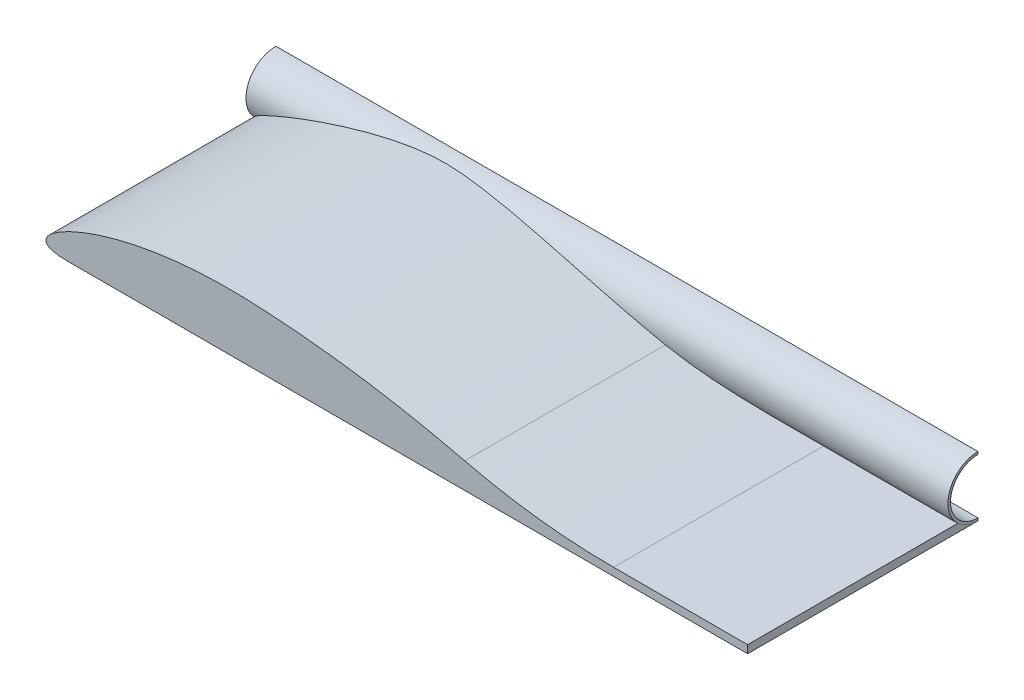
SolidWorks part; units mm, degrees
ref_plane "Front Plane" through (0, 0, 0) normal (0, 0, 1) x (1, 0, 0)
ref_plane "Top Plane" through (0, 0, 0) normal (0, 1, 0) x (1, 0, 0)
ref_plane "Right Plane" through (0, 0, 0) normal (1, 0, 0) x (0, 0, -1)
curve "Curve1"
  spline degree 3 poles (302.9843, 0.2066, 0) (305.2463, -0.0888, 0) (303.0423, 0.5058, 0) (301.2607, 1.1313, 0) (296.8595, 2.4314, 0) (291.4283, 4.0595, 0) (284.2715, 6.1062, 0) (275.7591, 8.441, 0) (265.8676, 11.0139, 0) (254.7283, 13.724, 0) (242.4522, 16.5013, 0) (229.1619, 19.2495, 0) (215.0022, 21.8919, 0) (200.1221, 24.3477, 0) (184.6818, 26.5449, 0) (168.8517, 28.4234, 0) (152.8082, 29.9307, 0) (136.7266, 31.0049, 0) (120.7051, 31.6889, 0) (104.9137, 31.6962, 0) (89.5649, 30.8862, 0) (74.9378, 29.3709, 0) (61.2207, 27.2233, 0) (48.5868, 24.554, 0) (37.1861, 21.5011, 0) (27.1553, 18.1971, 0) (18.5969, 14.8045, 0) (11.6064, 11.436, 0) (6.2054, 8.2632, 0) (2.4621, 5.3102, 0) (0.1728, 2.7181, 0) (-0.3667, -0.1067, 0) (1.6185, -2.1752, 0) (4.9031, -3.1118, 0) (9.5405, -3.659, 0) (15.6223, -3.6847, 0) (23.0877, -3.3095, 0) (31.8617, -2.5607, 0) (41.8437, -1.5362, 0) (52.932, -0.3245, 0) (65.0085, 0.9827, 0) (77.9641, 2.2775, 0) (91.674, 3.4466, 0) (106.0204, 4.4121, 0) (120.9553, 5.0518, 0) (136.3391, 5.4103, 0) (152.0077, 5.7293, 0) (167.7158, 5.8914, 0) (183.2867, 5.9078, 0) (198.553, 5.7595, 0) (213.3478, 5.4574, 0) (227.5084, 5.0134, 0) (240.8771, 4.4585, 0) (253.3023, 3.8196, 0) (264.6365, 3.1406, 0) (274.7593, 2.4517, 0) (283.5118, 1.8033, 0) (290.9024, 1.2074, 0) (296.5367, 0.7424, 0) (301.0977, 0.3102, 0) (302.9843, 0.2066, 0) (305.2463, -0.0888, 0) (303.0423, 0.5058, 0) knots -0.012269 -0.005489 -0.001366 0 0.001375 0.005484 0.012273 0.021682 0.033581 0.047831 0.064306 0.082777 0.103064 0.124929 0.148149 0.172445 0.197572 0.223269 0.249228 0.275186 0.300901 0.326463 0.351222 0.374906 0.39727 0.418072 0.43708 0.454093 0.46892 0.481392 0.491447 0.499024 0.504294 0.507922 0.51154 0.516781 0.524216 0.533992 0.546034 0.56022 0.576403 0.594371 0.613951 0.634917 0.657089 0.68023 0.704175 0.72909 0.754354 0.779668 0.80476 0.829359 0.853209 0.876041 0.897604 0.917662 0.93597 0.95231 0.966503 0.97835 0.987731 0.994511 0.998634 1 1.001375 1.005484 1.012273 periodic
sketch "Sketch1" plane through (0, 0, 0) normal (0, 0, 1) x (1, 0, 0)
  line L0 (397.4027, 0) -> (397.4027, -11.2558) construction
  line L1 (397.4027, -11.2558) -> (0, -11.2558) construction
  line L2 (0, -11.2558) -> (0, 0) construction
  line L3 (397.4027, 0) -> (397.4027, 42.136) construction
  line L4 (397.4027, 42.136) -> (0, 42.136) construction
  line L5 (0, 42.136) -> (0, 0) construction
  line L6 (16.8245, -3.584) -> (563.88, -3.584)
  line L7 (563.88, -3.584) -> (563.88, 2.766)
  line L8 (563.88, 2.766) -> (388.5279, 2.766)
  line L9 (397.4027, 0) -> (0, 0) construction
  spline S1 degree 3 poles (395.0322, 0.2772) (397.9852, -0.1177) (395.1091, 0.6677) (392.7847, 1.492) (387.0417, 3.208) (379.9549, 5.3566) (370.6158, 8.059) (359.5074, 11.1431) (346.5989, 14.5439) (332.0611, 18.1288) (316.0389, 21.8064) (298.6919, 25.4499) (280.2091, 28.9588) (260.7844, 32.227) (240.6272, 35.1598) (219.9595, 37.6778) (199.0115, 39.7119) (178.012, 41.1805) (157.0894, 42.1393) (136.4647, 42.2132) (116.4146, 41.2179) (97.3043, 39.2985) (79.38, 36.5495) (62.8681, 33.1148) (47.9656, 29.1739) (34.851, 24.8995) (23.6593, 20.5034) (14.5153, 16.1325) (7.4482, 12.0105) (2.5471, 8.169) (-0.4534, 4.7928) (-1.1696, 1.1056) (1.4149, -1.6041) (5.701, -2.8408) (11.7555, -3.5745) (19.6988, -3.6327) (29.4507, -3.1732) (40.9133, -2.231) (53.9547, -0.9336) (68.4418, 0.6036) (84.2201, 2.2618) (101.1464, 3.9) (119.0574, 5.371) (137.7989, 6.5735) (157.3077, 7.348) (177.4016, 7.7535) (197.8673, 8.1063) (218.3839, 8.2538) (238.7209, 8.2118) (258.6593, 7.9558) (277.9812, 7.5009) (296.4742, 6.8632) (313.9325, 6.084) (330.1583, 5.1987) (344.9588, 4.2658) (358.1772, 3.3246) (369.606, 2.4422) (379.2564, 1.6336) (386.6132, 1.0034) (392.5685, 0.4203) (395.0322, 0.2772) (397.9852, -0.1177) (395.1091, 0.6677) knots -0.012269 -0.005489 -0.001366 0 0.001375 0.005484 0.012273 0.021682 0.033581 0.047831 0.064306 0.082777 0.103064 0.124929 0.148149 0.172445 0.197572 0.223269 0.249228 0.275186 0.300901 0.326463 0.351222 0.374906 0.39727 0.418072 0.43708 0.454093 0.46892 0.481392 0.491447 0.499024 0.504294 0.507922 0.51154 0.516781 0.524216 0.533992 0.546034 0.56022 0.576403 0.594371 0.613951 0.634917 0.657089 0.68023 0.704175 0.72909 0.754354 0.779668 0.80476 0.829359 0.853209 0.876041 0.897604 0.917662 0.93597 0.95231 0.966503 0.97835 0.987731 0.994511 0.998634 1 1.001375 1.005484 1.012273 only from (397.4027, 0) to (397.4027, 0)
  dimension "D1" = 45.72
  dimension "D2" = 563.88
  dimension "D3" = 6.35
  dimension "D4" = 397.4027
extrude "Boss-Extrude1" add sketch "Sketch1" along normal blind 185.42 contours S1 L6 L7 L8 | S1
fillet "Fillet1" radius 508 1 edges at (388.5279, 2.766, 92.71)
sketch "Sketch2" plane through (563.88, 0, 0) normal (1, 0, 0) x (0, 0, -1)
  line L0 (0, -3.584) -> (0, 44.676)
  arc A0 (0, -3.584) -> (0, 44.676) centre (0, 20.546) cw
  line M2 (0, -3.584) -> (0, 2.766)
  line M3 (0, 2.766) -> (-185.42, 2.766)
  dimension "D1" = 48.26
extrude "Boss-Extrude2" add sketch "Sketch2" along normal through all and the other way through all contours A0 M2 M3 | A0 L0 M3
sketch "Sketch3" plane through (563.88, 0, 0) normal (1, 0, 0) x (0, 0, -1)
  line L0 (0, -3.584) -> (0, 44.676) construction
  line L1 (0, -1.552) -> (0, 42.644)
  arc A0 (0, -1.552) -> (0, 42.644) centre (0, 20.546) cw
  arc A1 (-16.3134, 2.766) -> (0, -3.584) centre (0, 20.546) ccw construction
  dimension "D1" = 2.032
extrude "Cut-Extrude1" cut sketch "Sketch3" against normal through all
